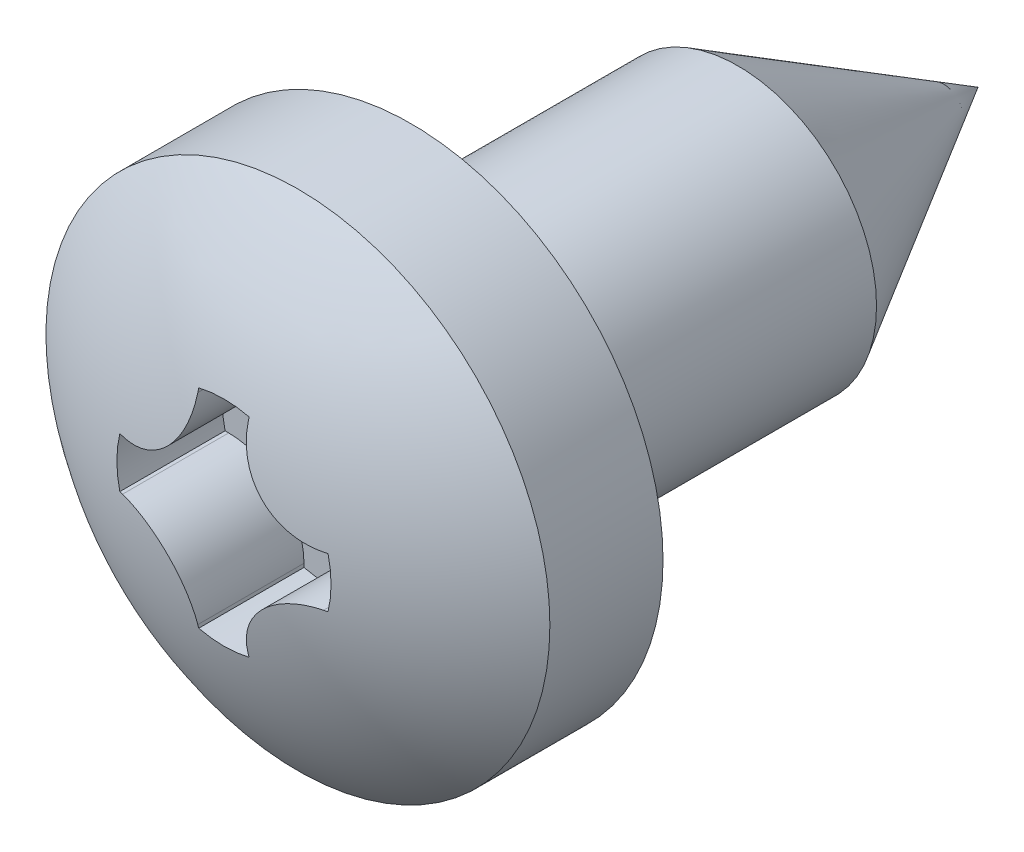
SolidWorks part; units mm, degrees
revolve "基体-旋转" add sketch "草图8" angle 360 about L0
sketch "草图8" plane through (0, 0, 0) normal (1, 0, 0) x (0, 0, -1)
  line L0 (-11.71, 0) -> (1.33, 0) construction
  line L1 (0, 0) -> (-6.1, 0)
  line L4 (-5.398, 2) -> (-4.5, 2)
  line L5 (-4.5, 2) -> (-4.5, 1.1)
  line L6 (-4.5, 1.1) -> (-1.9053, 1.1)
  line L7 (-1.9053, 1.1) -> (0, 0)
  arc A0 (-6.1, 0) -> (-5.398, 2) centre (-2.9, 0) cw
  dimension "D4" = 3.2
  dimension "D1" = 4.5
  dimension "D2" = 30
  dimension "D5" = 2.2
  dimension "D3" = 4
  dimension "D6" = 1.6
cosmetic thread "装饰螺纹线1" parameters "D1"=1.7, "D2"=1.9052
extrude "切除-拉伸2" cut sketch "草图7" against normal blind 0.95
sketch "草图7" plane through (0, 0, 6.1) normal (0, 0, 1) x (1, 0, 0)
  line L0 (-7.1, 0) -> (5.9, 0) construction
  line L1 (0, 7.5) -> (0, -7) construction
  line L2 (0.2, 0.8261) -> (0.2, 0.7975)
  line L3 (0, 0) -> (4.9858, 4.9858) construction
  line L4 (0.8261, 0.2) -> (0.7975, 0.2)
  line L5 (0.8261, -0.2) -> (0.7975, -0.2)
  line L6 (0.2, -0.8261) -> (0.2, -0.7975)
  line L7 (-0.2, -0.8261) -> (-0.2, -0.7975)
  line L8 (-0.8261, -0.2) -> (-0.7975, -0.2)
  line L9 (-0.8261, 0.2) -> (-0.7975, 0.2)
  line L10 (-0.2, 0.8261) -> (-0.2, 0.7975)
  line L11 (0, 0) -> (-4.9858, 4.9858) construction
  arc A0 (-0.2, 0.8261) -> (0.2, 0.8261) centre (0, 0) cw
  arc A1 (0.8261, -0.2) -> (0.8261, 0.2) centre (0, 0) ccw
  arc A2 (0.7975, 0.2) -> (0.2, 0.7975) centre (0.7975, 0.7975) cw
  arc A3 (-0.7975, 0.2) -> (-0.2, 0.7975) centre (-0.7975, 0.7975) ccw
  arc A4 (-0.2, -0.8261) -> (0.2, -0.8261) centre (0, 0) ccw
  arc A5 (0.7975, -0.2) -> (0.2, -0.7975) centre (0.7975, -0.7975) ccw
  arc A6 (-0.8261, -0.2) -> (-0.8261, 0.2) centre (0, 0) cw
  arc A7 (-0.7975, -0.2) -> (-0.2, -0.7975) centre (-0.7975, -0.7975) cw
  dimension "D10" = 0.85
  dimension "D1" = 0.5975
  dimension "D2" = 0.5975
material "冷镦钢"
ref_plane "前视" through (0, 0, 0) normal (0, 0, 1) x (1, 0, 0)
ref_plane "上视" through (0, 0, 0) normal (0, 1, 0) x (1, 0, 0)
ref_plane "右视" through (0, 0, 0) normal (1, 0, 0) x (0, 0, -1)
sketch "尺寸草图" plane through (0, 0, 0) normal (1, 0, 0) x (0, 0, -1)
  line L0 (-4.5, 4) -> (-4.5, 0)
  line L1 (-4.5, 0) -> (0, 0)
  line L2 (0, 0) -> (0, 2.2)
  point P4 (-2.9, 0)
  point P6 (0, 0.8)
  point P7 (-3.7, 0)
  point P8 (-4.5, 3.9)
  point P9 (-4.5, 0.8)
  point P10 (-1.7, 0)
  point P11 (-0.95, 0)
  point P12 (-4.1, 0)
  point P13 (-1.7, 0)
  point P14 (-2.5, 0)
  dimension "l" = 4.5
  dimension "E" = 4
  dimension "K" = 1.6
  dimension "d" = 2.2
  dimension "P" = 0.8
  dimension "A" = 0.8
  dimension "R" = 0.1
  dimension "Rf" = 3.2
  dimension "HM" = 1.7
  dimension "HH" = 0.95
  dimension "HE" = 0.4
  dimension "Da" = 2.8
  dimension "Yc" = 2
ref_plane "基准面6" through (0, 0, 6.1) normal (0, 0, 1) x (1, 0, 0)
sketch "草图9" plane through (0, 0, 0) normal (1, 0, 0) x (0, 0, -1)
  line L0 (-3.7, 1.1) -> (-2.9, 1.1)
  line L1 (-3.7, 1.1) -> (-3.4, 0.7)
  line L2 (-3.2, 0.7) -> (-3.4, 0.7)
  line L3 (-3.2, 0.7) -> (-2.9, 1.1)
  line L4 (-11.71, 0) -> (1.33, 0) construction
  line L5 (-4.5, -2) -> (-4.5, 2) construction
  line L6 (-6.912, 0) -> (-2.6011, 0) construction
  line L7 (-5.15, 0) -> (-5.985, 0) construction
  dimension "D1" = 0.8
  dimension "D2" = 0.2
  dimension "D4" = 1.1
  dimension "D5" = 0.8
revolve "切除-旋转1" [suppressed] cut sketch "草图9" angle 360 about L6
pattern_linear "阵列(线性)1" [suppressed] count 4 spacing 1
fillet "圆角1" radius 0.1 1 edges at (1.1, 0, 4.5)
equation "\"D16@基准面6\" = \"l@尺寸草图\"+\"K@尺寸草图\""
equation "\"D1@草图8\" = \"l@尺寸草图\""
equation "\"D6@草图8\" = \"K@尺寸草图\""
equation "\"D5@草图8\" = \"d@尺寸草图\""
equation "\"D3@草图8\" = \"E@尺寸草图\""
equation "\"D4@草图8\" = \"Rf@尺寸草图\""
equation "\"D10@草图7\" = \"HM@尺寸草图\"/2"
equation "\"D1@切除-拉伸2\" = \"HH@尺寸草图\""
equation "\"D1@草图9\" = \"P@尺寸草图\""
equation "\"D2@草图9\" = \"D1@草图9\"/4"
equation "\"D3@草图9\" = \"D1@草图9\"/2"
equation "\"D4@草图9\" = \"d@尺寸草图\"/2"
equation "\"D5@草图9\" = \"A@尺寸草图\""
equation "\"D3@阵列(线性)1\" = \"A@尺寸草图\"*5/4"
equation "\"D1@阵列(线性)1\" = (\"l@尺寸草图\"-\"A@尺寸草图\")/\"D3@阵列(线性)1\""
equation "\"D2@装饰螺纹线1\" = \"d@尺寸草图\"*0.866"
equation "\"D1@装饰螺纹线1\" = \"l@尺寸草图\"-\"Yc@尺寸草图\"-\"A@尺寸草图\""
equation "\"D1@圆角1\" = \"R@尺寸草图\""
